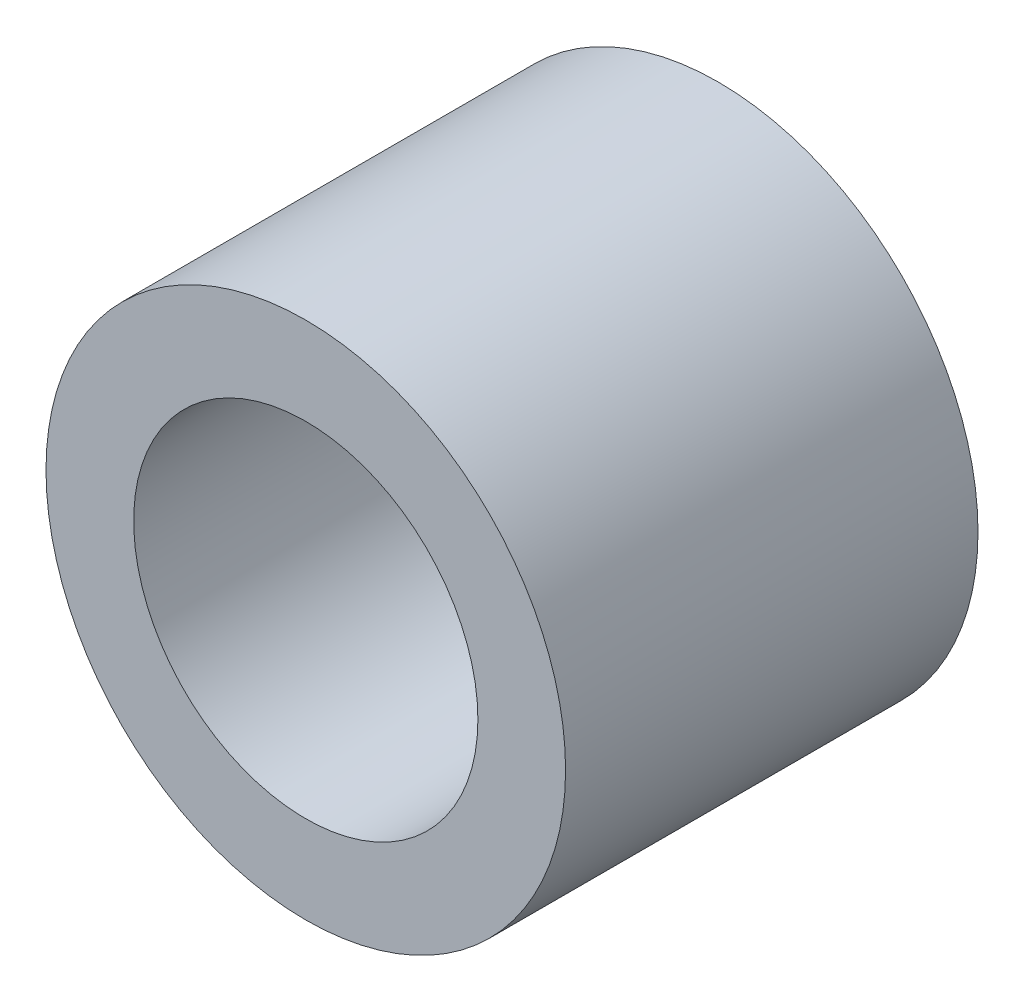
SolidWorks part; units mm, degrees
material "3003-H12, Barre (SS)"
ref_plane "Plan de face" through (0, 0, 0) normal (0, 0, 1) x (1, 0, 0)
ref_plane "Plan de dessus" through (0, 0, 0) normal (0, 1, 0) x (1, 0, 0)
ref_plane "Plan de droite" through (0, 0, 0) normal (1, 0, 0) x (0, 0, -1)
sketch "Esquisse1" plane through (0, 0, 0) normal (0, 0, 1) x (1, 0, 0)
  circle A0 centre (0, 0) radius 2.65
  circle A1 centre (0, 0) radius 4
  dimension "D1" = 8
  dimension "D2" = 5.3
extrude "Boss.-Extru.1" add sketch "Esquisse1" along normal mid plane 6.35
